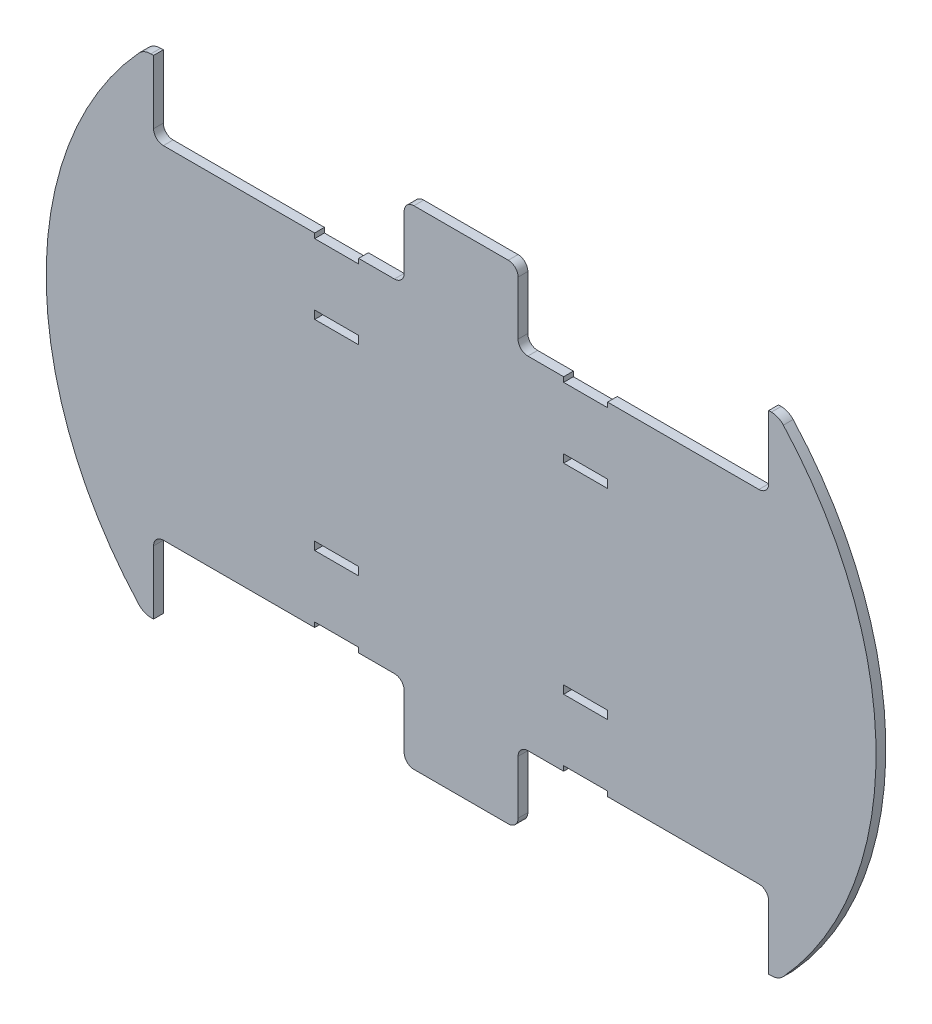
SolidWorks part; units mm, degrees
ref_plane "Ön Düzlem" through (0, 0, 0) normal (0, 0, 1) x (1, 0, 0)
ref_plane "Üst Düzlem" through (0, 0, 0) normal (0, 1, 0) x (1, 0, 0)
ref_plane "Sağ Düzlem" through (0, 0, 0) normal (1, 0, 0) x (0, 0, -1)
sketch "Çizim1" plane through (0, 0, 0) normal (0, 0, 1) x (1, 0, 0)
  line L0 (-17.5, 72) -> (-17.5, 55.5)
  line L1 (-95.3272, -75) -> (-94.5, -75)
  line L3 (-95.3272, 75) -> (-94.5, 75)
  line L6 (94.5, 75) -> (94.5, 55.5)
  line L7 (-14.5, 75) -> (14.5, 75)
  line L8 (17.5, 72) -> (17.5, 55.5)
  line L11 (-94.5, -75) -> (-94.5, -55.5)
  line L13 (-91.5, -52.5) -> (-45, -52.5)
  line L15 (91.5, 52.5) -> (45, 52.5)
  line L18 (94.5, -75) -> (95.3272, -75)
  line L19 (-14.5, -75) -> (14.5, -75)
  line L20 (-94.5, 55.5) -> (-94.5, 75)
  line L21 (-17.5, -55.5) -> (-17.5, -72)
  line L22 (17.5, -55.5) -> (17.5, -72)
  line L23 (94.5, -55.5) -> (94.5, -75)
  line L24 (-20.5, 52.5) -> (-31.5, 52.5)
  line L25 (20.5, -52.5) -> (31.5, -52.5)
  line L27 (94.5, 75) -> (95.3272, 75)
  line L29 (45, -52.5) -> (91.5, -52.5)
  line L31 (-45, -52.5) -> (-45, -51)
  line L33 (-31.5, -51) -> (-31.5, -52.5)
  line L37 (-31.5, -51) -> (-45, -51)
  line L38 (45, 29.5) -> (31.5, 29.5)
  line L39 (-31.5, -32) -> (-45, -32)
  line L40 (-45, -32) -> (-45, -29.5)
  line L41 (-45, -29.5) -> (-31.5, -29.5)
  line L42 (-31.5, -29.5) -> (-31.5, -32)
  line L43 (-31.5, -52.5) -> (-20.5, -52.5)
  line L44 (-45, 52.5) -> (-45, 51)
  line L45 (-31.5, 51) -> (-31.5, 52.5)
  line L46 (-31.5, 51) -> (-45, 51)
  line L47 (-31.5, 29.5) -> (-31.5, 32)
  line L48 (-31.5, 32) -> (-45, 32)
  line L49 (-45, 32) -> (-45, 29.5)
  line L50 (-45, 29.5) -> (-31.5, 29.5)
  line L51 (45, 32) -> (45, 29.5)
  line L52 (31.5, 32) -> (45, 32)
  line L53 (31.5, 29.5) -> (31.5, 32)
  line L54 (31.5, 51) -> (45, 51)
  line L55 (31.5, 51) -> (31.5, 52.5)
  line L56 (45, 52.5) -> (45, 51)
  line L57 (31.5, -29.5) -> (31.5, -32)
  line L58 (45, -29.5) -> (31.5, -29.5)
  line L59 (45, -32) -> (45, -29.5)
  line L60 (31.5, -32) -> (45, -32)
  line L61 (31.5, -51) -> (45, -51)
  line L62 (31.5, -51) -> (31.5, -52.5)
  line L63 (45, -52.5) -> (45, -51)
  line L65 (31.5, 52.5) -> (20.5, 52.5)
  line L66 (-45, 52.5) -> (-91.5, 52.5)
  arc A0 (-91.5, 52.5) -> (-94.5, 55.5) centre (-91.5, 55.5) cw
  arc A1 (-17.5, 55.5) -> (-20.5, 52.5) centre (-20.5, 55.5) cw
  arc A2 (-17.5, 72) -> (-14.5, 75) centre (-14.5, 72) cw
  arc A3 (14.5, 75) -> (17.5, 72) centre (14.5, 72) cw
  arc A4 (17.5, 55.5) -> (20.5, 52.5) centre (20.5, 55.5) ccw
  arc A5 (91.5, 52.5) -> (94.5, 55.5) centre (91.5, 55.5) ccw
  arc A6 (91.5, -52.5) -> (94.5, -55.5) centre (91.5, -55.5) cw
  arc A7 (17.5, -55.5) -> (20.5, -52.5) centre (20.5, -55.5) cw
  arc A8 (17.5, -72) -> (14.5, -75) centre (14.5, -72) cw
  arc A9 (-17.5, -72) -> (-14.5, -75) centre (-14.5, -72) ccw
  arc A10 (-17.5, -55.5) -> (-20.5, -52.5) centre (-20.5, -55.5) ccw
  arc A11 (-91.5, -52.5) -> (-94.5, -55.5) centre (-91.5, -55.5) ccw
  arc A12 (-99.0176, 73.3735) -> (-99.0176, -73.3735) centre (-18.75, 0) ccw
  arc A13 (99.0176, 73.3735) -> (99.0176, -73.3735) centre (18.75, 0) cw
  arc A14 (-95.3272, 75) -> (-99.0176, 73.3735) centre (-95.3272, 70) ccw
  arc A15 (-99.0176, -73.3735) -> (-95.3272, -75) centre (-95.3272, -70) ccw
  arc A16 (95.3272, -75) -> (99.0176, -73.3735) centre (95.3272, -70) ccw
  arc A17 (99.0176, 73.3735) -> (95.3272, 75) centre (95.3272, 70) ccw
  point P0 (0, 0)
  point P11 (-127.5, -37.5)
  point P27 (-17.5, 52.5)
  point P40 (94.5, -52.5)
  point P43 (17.5, -52.5)
  dimension "D3" = 2.5
  dimension "D1" = 2.5
  dimension "D2" = 2.5
  dimension "D4" = 2.5
extrude "Yükseklik-Ekstrüzyon1" add sketch "Çizim1" along normal blind 3
